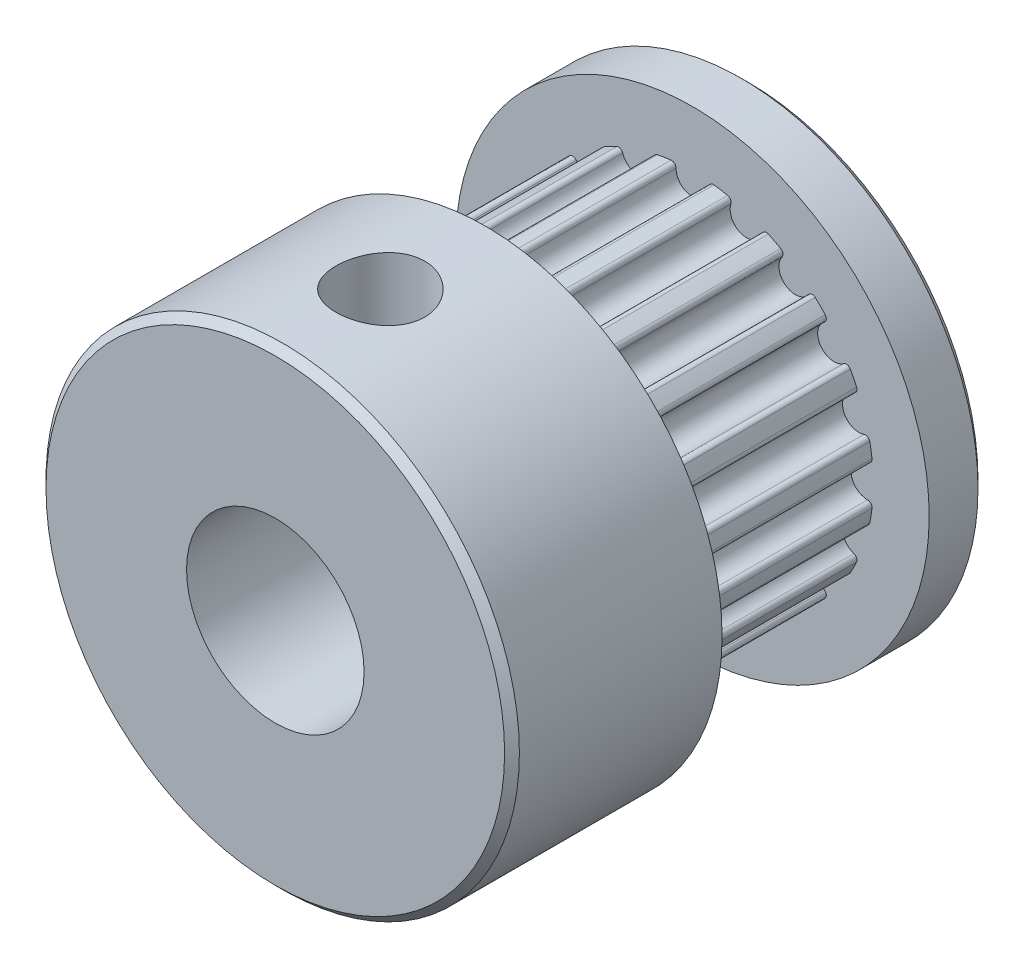
SolidWorks part; units mm, degrees
ref_plane "Front Plane" through (0, 0, 0) normal (0, 0, 1) x (1, 0, 0)
ref_plane "Top Plane" through (0, 0, 0) normal (0, 1, 0) x (1, 0, 0)
ref_plane "Right Plane" through (0, 0, 0) normal (1, 0, 0) x (0, 0, -1)
sketch "Sketch1" plane through (0, 0, 0) normal (0, 1, 0) x (1, 0, 0)
  line L0 (8, 1.9) -> (0, 1.9)
  line L1 (0, 1.9) -> (0, 0)
  line L2 (0, 0) -> (8, 0)
  line L3 (8, 0) -> (8, 1.9)
  line L4 (0, 1.9) -> (0, 0) construction
  dimension "D1" = 1.9
  dimension "D2" = 8
revolve "Revolve1" add sketch "Sketch1" angle 360 about L4
sketch "Sketch2" plane through (0, 0, 0) normal (0, 0, 1) x (1, 0, 0)
  arc A0 (0.5276, -6.0872) -> (-0.5276, -6.0872) centre (0, -5.915) ccw
  arc A1 (-0.5276, -6.0872) -> (-1.3792, -5.9523) centre (0, 0) cw
  arc A2 (-1.3792, -5.9523) -> (-2.3828, -5.6262) centre (-1.8278, -5.6255) ccw
  arc A3 (-2.3828, -5.6262) -> (-3.1511, -5.2348) centre (0, 0) cw
  arc A4 (-3.1511, -5.2348) -> (-4.0048, -4.6145) centre (-3.4767, -4.7853) ccw
  arc A5 (-4.0048, -4.6145) -> (-4.6145, -4.0048) centre (0, 0) cw
  arc A6 (-4.6145, -4.0048) -> (-5.2348, -3.1511) centre (-4.7853, -3.4767) ccw
  arc A7 (-5.2348, -3.1511) -> (-5.6262, -2.3828) centre (0, 0) cw
  arc A8 (-5.6262, -2.3828) -> (-5.9523, -1.3792) centre (-5.6255, -1.8278) ccw
  arc A9 (-5.9523, -1.3792) -> (-6.0872, -0.5276) centre (0, 0) cw
  arc A10 (-6.0872, -0.5276) -> (-6.0872, 0.5276) centre (-5.915, 0) ccw
  arc A11 (-6.0872, 0.5276) -> (-5.9523, 1.3792) centre (0, 0) cw
  arc A12 (-5.9523, 1.3792) -> (-5.6262, 2.3828) centre (-5.6255, 1.8278) ccw
  arc A13 (-5.6262, 2.3828) -> (-5.2348, 3.1511) centre (0, 0) cw
  arc A14 (-5.2348, 3.1511) -> (-4.6145, 4.0048) centre (-4.7853, 3.4767) ccw
  arc A15 (-4.6145, 4.0048) -> (-4.0048, 4.6145) centre (0, 0) cw
  arc A16 (-4.0048, 4.6145) -> (-3.1511, 5.2348) centre (-3.4767, 4.7853) ccw
  arc A17 (-3.1511, 5.2348) -> (-2.3828, 5.6262) centre (0, 0) cw
  arc A18 (-2.3828, 5.6262) -> (-1.3792, 5.9523) centre (-1.8278, 5.6255) ccw
  arc A19 (-1.3792, 5.9523) -> (-0.5276, 6.0872) centre (0, 0) cw
  arc A20 (-0.5276, 6.0872) -> (0.5276, 6.0872) centre (0, 5.915) ccw
  arc A21 (0.5276, 6.0872) -> (1.3792, 5.9523) centre (0, 0) cw
  arc A22 (1.3792, 5.9523) -> (2.3828, 5.6262) centre (1.8278, 5.6255) ccw
  arc A23 (2.3828, 5.6262) -> (3.1511, 5.2348) centre (0, 0) cw
  arc A24 (3.1511, 5.2348) -> (4.0048, 4.6145) centre (3.4767, 4.7853) ccw
  arc A25 (4.0048, 4.6145) -> (4.6145, 4.0048) centre (0, 0) cw
  arc A26 (4.6145, 4.0048) -> (5.2348, 3.1511) centre (4.7853, 3.4767) ccw
  arc A27 (5.2348, 3.1511) -> (5.6262, 2.3828) centre (0, 0) cw
  arc A28 (5.6262, 2.3828) -> (5.9523, 1.3792) centre (5.6255, 1.8278) ccw
  arc A29 (5.9523, 1.3792) -> (6.0872, 0.5276) centre (0, 0) cw
  arc A30 (6.0872, 0.5276) -> (6.0872, -0.5276) centre (5.915, 0) ccw
  arc A31 (6.0872, -0.5276) -> (5.9523, -1.3792) centre (0, 0) cw
  arc A32 (5.9523, -1.3792) -> (5.6262, -2.3828) centre (5.6255, -1.8278) ccw
  arc A33 (5.6262, -2.3828) -> (5.2348, -3.1511) centre (0, 0) cw
  arc A34 (5.2348, -3.1511) -> (4.6145, -4.0048) centre (4.7853, -3.4767) ccw
  arc A35 (4.6145, -4.0048) -> (4.0048, -4.6145) centre (0, 0) cw
  arc A36 (4.0048, -4.6145) -> (3.1511, -5.2348) centre (3.4767, -4.7853) ccw
  arc A37 (3.1511, -5.2348) -> (2.3828, -5.6262) centre (0, 0) cw
  arc A38 (2.3828, -5.6262) -> (1.3792, -5.9523) centre (1.8278, -5.6255) ccw
  arc A39 (1.3792, -5.9523) -> (0.5276, -6.0872) centre (0, 0) cw
extrude "Boss-Extrude1" add sketch "Sketch2" along normal blind 7
ref_plane "Plane1" through (0, 0, 7) normal (0, 0, -1) x (-1, 0, 0)
sketch "Sketch3" plane through (0, 0, 7) normal (0, 0, -1) x (-1, 0, 0)
  circle A0 centre (0, 0) radius 8
extrude "Boss-Extrude2" add sketch "Sketch3" against normal blind 7.1
sketch "Sketch4" plane through (0, 0, 14.1) normal (0, 0, 1) x (1, 0, 0)
  circle A0 centre (0, 0) radius 3
  dimension "D1" = 6
extrude "Cut-Extrude1" cut sketch "Sketch4" against normal through all
hole_wizard "Ø3.0) Diameter Hole2" positions "Sketch7" profile "Sketch6" hole size "Ø3.0" standard "ANSI Metric"
sketch "Sketch7" plane through (0, 0, 0) normal (0, -1, 0) x (-1, 0, 0)
  line L0 (0, -7) -> (0, -14.1) construction
  line L1 (8, -7) -> (-8, -7) construction
  line L2 (-8, -14.1) -> (8, -14.1) construction
  point P0 (0, -10.55)
sketch "Sketch6" plane through (0, 0, 10.55) normal (1, 0, 0) x (0, 0, -1)
  line L0 (0, 0) -> (0, 8)
  line L1 (0, 8) -> (1.5, 8)
  line L2 (1.5, 8) -> (1.5, 0)
  line L5 (1.5, 0) -> (0, 0)
  line L11 (0, -6.35) -> (0, 107.95) construction
  dimension "Thru Hole Dia." = 3
  dimension "Thru Hole Depth" = 8
chamfer "Chamfer1" distance 0.25 angle 45 2 edges at (8, 0, 14.1) (8, 0, -1.9)
fillet "Fillet1" radius 0.15 40 edges at (-5.9523, 1.3792, 3.5) (-3.1511, -5.2348, 3.5) (-0.5276, 6.0872, 3.5) (1.3792, 5.9523, 3.5) (-5.6262, -2.3828, 3.5) (2.3828, 5.6262, 3.5) (-4.0048, 4.6145, 3.5) (0.5276, 6.0872, 3.5) (-1.3792, -5.9523, 3.5) (3.1511, 5.2348, 3.5) (-4.6145, -4.0048, 3.5) (4.0048, 4.6145, 3.5) (-6.0872, -0.5276, 3.5) (4.6145, 4.0048, 3.5) (-5.2348, 3.1511, 3.5) (5.2348, 3.1511, 3.5) (-2.3828, 5.6262, 3.5) (5.6262, 2.3828, 3.5) (-0.5276, -6.0872, 3.5) (5.9523, 1.3792, 3.5) (-2.3828, -5.6262, 3.5) (6.0872, 0.5276, 3.5) (-4.0048, -4.6145, 3.5) (6.0872, -0.5276, 3.5) (-5.2348, -3.1511, 3.5) (5.9523, -1.3792, 3.5) (-5.9523, -1.3792, 3.5) (5.6262, -2.3828, 3.5) (-6.0872, 0.5276, 3.5) (5.2348, -3.1511, 3.5) (-5.6262, 2.3828, 3.5) (4.6145, -4.0048, 3.5) (-4.6145, 4.0048, 3.5) (4.0048, -4.6145, 3.5) (-3.1511, 5.2348, 3.5) (2.3828, -5.6262, 3.5) (-1.3792, 5.9523, 3.5) (1.3792, -5.9523, 3.5) (0.5276, -6.0872, 3.5) (3.1511, -5.2348, 3.5)
ref_plane "Plane2" through (0, 0, 3.5) normal (0, 0, 1) x (1, 0, 0)
